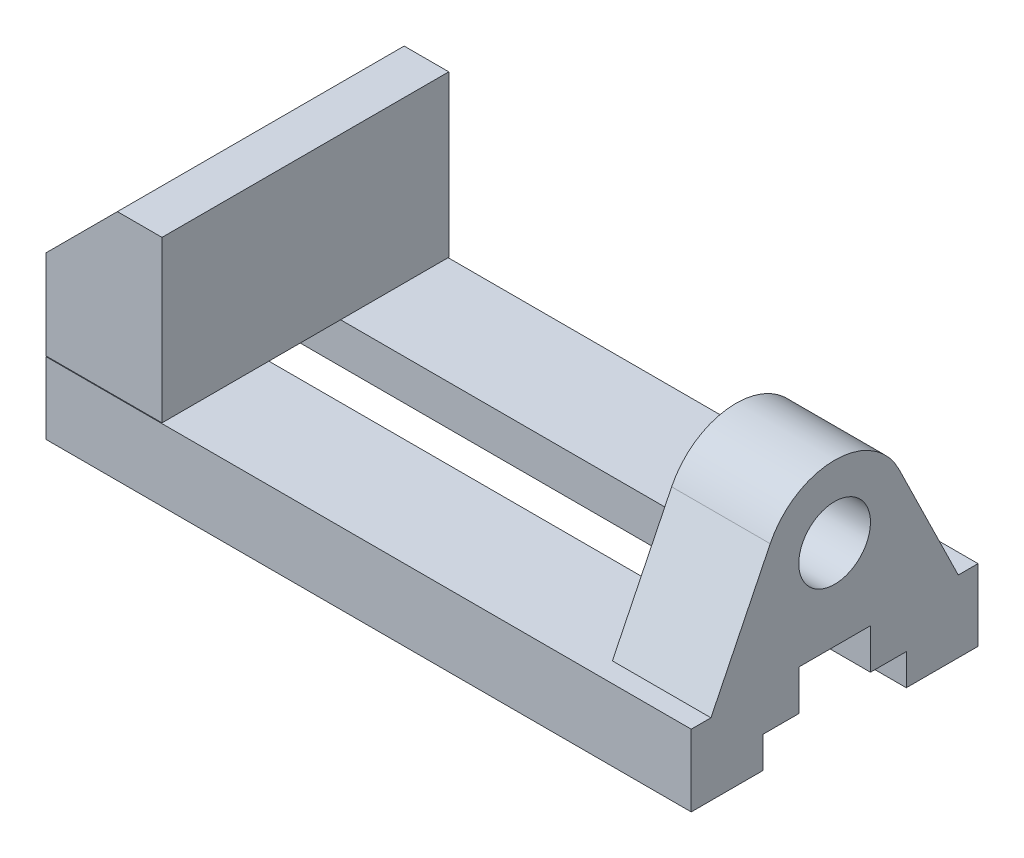
SolidWorks part; units mm, degrees
material "Gray Cast Iron"
ref_plane "Front Plane" through (0, 0, 0) normal (0, 0, 1) x (1, 0, 0)
ref_plane "Top Plane" through (0, 0, 0) normal (0, 1, 0) x (1, 0, 0)
ref_plane "Right Plane" through (0, 0, 0) normal (1, 0, 0) x (0, 0, -1)
sketch "Sketch1" plane through (0, 0, 0) normal (0, 0, 1) x (1, 0, 0)
  line L1 (72, 8) -> (-72, 8)
  line L2 (72, 8) -> (72, -8)
  line L3 (72, -8) -> (-72, -8)
  line L4 (-72, 8) -> (-72, -8)
  line L5 (72, 8) -> (-72, -8) construction
  line L6 (72, -8) -> (-72, 8) construction
  point P0 (0, 0)
  dimension "D1" = 16
  dimension "D2" = 144
extrude "Boss-Extrude1" add sketch "Sketch1" along normal mid plane 64
ref_plane "Plane1" through (0, 0, 32) normal (0, 0, 1) x (1, 0, 0)
sketch "Sketch2" plane through (0, 0, 32) normal (0, 0, 1) x (1, 0, 0)
  line L0 (-72, 8.15) -> (-46.1084, 8.15)
  line L6 (-56.0667, 44) -> (-72, 28.0667)
  line L8 (-72, 8.15) -> (-72, 28.0667)
  line L9 (-56.0667, 44) -> (-46.1084, 44)
  line L10 (-46.1084, 8.15) -> (-46.1084, 44)
  dimension "D1" = 9.9583
  dimension "D2" = 35.85
  dimension "D3" = 22.5331
  dimension "D4" = 46.1084
  dimension "D5" = 45
  dimension "D6" = 15.9333
  dimension "D7" = 19.9166
  dimension "D8" = 72
  dimension "D9" = 8.15
extrude "Boss-Extrude2" add sketch "Sketch2" against normal blind 64
ref_plane "Plane2" through (72, 0, 0) normal (1, 0, 0) x (0, 0, -1)
sketch "Sketch3" plane through (72, 0, 0) normal (1, 0, 0) x (0, 0, -1)
  line L0 (-27.5969, 8) -> (-32, 8)
  line L1 (-32, -8) -> (32, -8) construction
  line L2 (-32, 8) -> (-27.5969, 8) construction
  line L3 (-32, 8) -> (-32, -8)
  line L4 (27.5969, 8) -> (32, 8)
  line L5 (-32, 8.8) -> (-32, -8.8) construction
  line L6 (-32, 8) -> (32, 8) construction
  line L7 (27.5969, 8) -> (14.3722, 35.0314)
  line L8 (32, 8) -> (32, -8)
  line L9 (-32, -8) -> (32, -8)
  line L15 (0, 28) -> (0, 12) construction
  line L16 (-32, 1012.6082) -> (-32, 8) construction
  line L18 (-27.5969, 8) -> (-14.3722, 35.0314)
  line L19 (0, 67.6242) -> (21098.9131, 45314.3894) construction
  circle A0 centre (0, 28) radius 8
  arc A1 (14.3722, 35.0314) -> (-14.3722, 35.0314) centre (0, 28) ccw
  point P14 (0, 8)
  point P19 (0, 8)
  point P21 (0, 0)
  point P35 (-32, -1)
  dimension "D1" = 36
  dimension "D2" = 32
  dimension "D3" = 16
  dimension "D4" = 27.5969
  dimension "D5" = 27.5969
  dimension "D6" = 8
extrude "Boss-Extrude3" add sketch "Sketch3" against normal blind 22
sketch "Sketch4" plane through (72, 0, 0) normal (1, 0, 0) x (0, 0, -1)
  line L0 (-32, 8) -> (32, 8) construction
  line L1 (-32, 8.8) -> (-32, -8.8) construction
  line L2 (-32, 8) -> (-27.5969, 8) construction
  line L3 (8, 8) -> (-8, 8)
  line L4 (32, -8) -> (-32, -8) construction
  line L5 (-32, -8) -> (32, -8) construction
  line L6 (-16, -8) -> (16, -8)
  line L7 (-16, -8) -> (-16, -1)
  line L8 (-8, 8) -> (-8, -4.0342) construction
  line L9 (-16, -1) -> (-8, -1)
  line L10 (-8, -1) -> (-8, 8)
  line L11 (0, 8) -> (0, -10.9351) construction
  line L12 (8, -1) -> (8, 8)
  line L13 (16, -8) -> (16, -1)
  line L14 (16, -1) -> (8, -1)
  point P10 (0, 8)
  point P15 (0, -8)
  point P18 (0, -8)
  dimension "D1" = 16
  dimension "D2" = 32
  dimension "D3" = 7
extrude "Cut-Extrude1" cut sketch "Sketch4" against normal through all
ref_plane "Plane3" through (0, 0, 22) normal (0, 0, 1) x (1, 0, 0)
sketch "Sketch6" plane through (0, 0, 22) normal (0, 0, 1) x (1, 0, 0)
  line L0 (34, -1008) -> (34, -8) construction
  line L1 (34, -2.14) -> (34, -8)
  line L2 (34, -8) -> (30.65, -8)
  line L3 (-72, -8) -> (72, -8) construction
  line L4 (30.65, -8) -> (30.65, 2)
  line L6 (34, -2.14) -> (34, 49992) construction
  line L7 (30.65, 2) -> (34, 3.9341)
  line L8 (34, 3.9341) -> (34, -2.14)
  dimension "D1" = 38
  dimension "D2" = 3.35
  dimension "D3" = 60
  dimension "D4" = 6.0741
revolve "Cut-Revolve1" cut sketch "Sketch6" angle 360 about L8
sketch "Sketch7" plane through (0, 0, 22) normal (0, 0, 1) x (1, 0, 0)
  line L0 (-1, -8) -> (-1, 49992) construction
  line L2 (34, -2.14) -> (34, 249992) construction
  line L3 (34, 3.9341) -> (30.65, 2) construction
  line L4 (30.65, 2) -> (30.65, -8) construction
  line L5 (30.65, -8) -> (34, -8) construction
  line L6 (34, -8) -> (34, 3.9341) construction
  line L7 (-32.65, -8) -> (-36, -8) construction
  line L8 (-36, -8) -> (-36, 3.9341) construction
  line L9 (-32.65, 2) -> (-32.65, -8) construction
  line L10 (-36, 3.9341) -> (-32.65, 2) construction
  line L11 (-36, 3.9341) -> (-36, -8)
  line L12 (-36, -8) -> (-32.65, -8)
  line L13 (-32.65, -8) -> (-32.65, 2)
  line L14 (-32.65, 2) -> (-36, 3.9341)
  dimension "D1" = 35
revolve "Cut-Revolve2" cut sketch "Sketch7" angle 360 about L11
mirror "Mirror2" about plane through (0, 0, 0) normal (0, 0, 1) of "Cut-Revolve1", "Cut-Revolve2"
